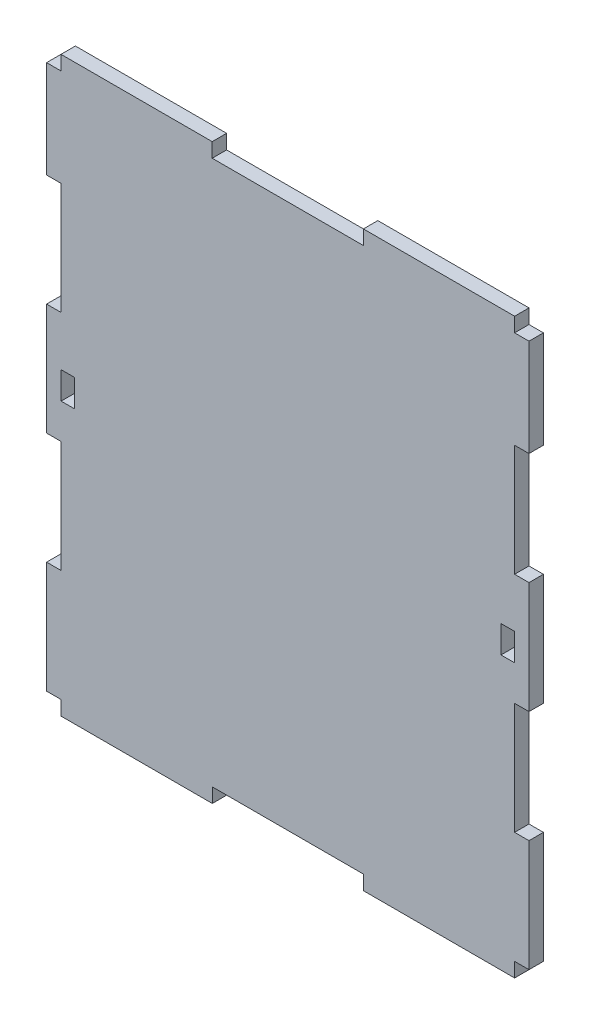
SolidWorks part; units mm, degrees
ref_plane "Front Plane" through (0, 0, 0) normal (0, 0, 1) x (1, 0, 0)
ref_plane "Top Plane" through (0, 0, 0) normal (0, 1, 0) x (1, 0, 0)
ref_plane "Right Plane" through (0, 0, 0) normal (1, 0, 0) x (0, 0, -1)
sketch "Sketch1" plane through (0, 0, 0) normal (0, 0, 1) x (1, 0, 0)
  line L0 (0, 120) -> (-3.175, 120)
  line L1 (0, 0) -> (100, 0) construction
  line L2 (0, 0) -> (0, 120) construction
  line L3 (0, 120) -> (100, 120) construction
  line L4 (100, 0) -> (100, 120) construction
  line L5 (-3.175, 120) -> (-3.175, 98.54)
  line L6 (-3.175, 98.54) -> (0, 98.54)
  line L7 (0, 98.54) -> (0, 73.905)
  line L8 (0, 73.905) -> (-3.175, 73.905)
  line L9 (-3.175, 73.905) -> (-3.175, 49.27)
  line L10 (-3.175, 49.27) -> (0, 49.27)
  line L11 (0, 49.27) -> (0, 24.635)
  line L12 (0, 24.635) -> (-3.175, 24.635)
  line L13 (-3.175, 24.635) -> (-3.175, 0)
  line L14 (-3.175, 0) -> (0, 0)
  line L15 (100, 120) -> (103.175, 120)
  line L16 (103.175, 120) -> (103.175, 98.54)
  line L17 (103.175, 98.54) -> (100, 98.54)
  line L18 (100, 98.54) -> (100, 73.905)
  line L19 (100, 73.905) -> (103.175, 73.905)
  line L20 (103.175, 73.905) -> (103.175, 49.27)
  line L21 (103.175, 49.27) -> (100, 49.27)
  line L22 (100, 49.27) -> (100, 24.635)
  line L23 (100, 24.635) -> (103.175, 24.635)
  line L24 (103.175, 24.635) -> (103.175, 0)
  line L25 (103.175, 0) -> (100, 0)
  line L26 (0, 120) -> (0, 123.175)
  line L27 (0, 123.175) -> (33.3333, 123.175)
  line L28 (33.3333, 123.175) -> (33.3333, 120)
  line L29 (33.3333, 120) -> (66.6667, 120)
  line L30 (66.6667, 120) -> (66.6667, 123.175)
  line L31 (66.6667, 123.175) -> (100, 123.175)
  line L32 (100, 123.175) -> (100, 120)
  line L33 (0, 0) -> (0, -3.175)
  line L34 (0, -3.175) -> (33.3588, -3.175)
  line L35 (33.3588, -3.175) -> (33.3588, 0)
  line L36 (33.3588, 0) -> (66.6921, 0)
  line L37 (66.6921, 0) -> (66.6921, -3.175)
  line L38 (66.6921, -3.175) -> (100, -3.175)
  line L39 (100, -3.175) -> (100, 0)
  line L40 (103.2005, 60) -> (-3.175, 60) construction
  line L41 (97, 63) -> (100, 63)
  line L42 (97, 63) -> (97, 57)
  line L43 (97, 57) -> (100, 57)
  line L44 (100, 63) -> (100, 57)
  line L45 (50, 120) -> (50.0255, 0) construction
  line L46 (3.0242, 62.98) -> (3.0268, 56.98)
  line L47 (3.0268, 56.98) -> (0.0268, 56.9788)
  line L48 (0.0242, 62.9788) -> (0.0268, 56.9788)
  line L49 (3.0242, 62.98) -> (0.0242, 62.9788)
  point P49 (50.0127, 60)
  dimension "D10" = 3
  dimension "D1" = 120
  dimension "D2" = 100
  dimension "D3" = 21.46
  dimension "D4" = 3.175
  dimension "D5" = 3.175
  dimension "D6" = 3.175
  dimension "D7" = 3.175
  dimension "D8" = 6
  dimension "D9" = 3
extrude "Boss-Extrude1" add sketch "Sketch1" along normal blind 3.175
